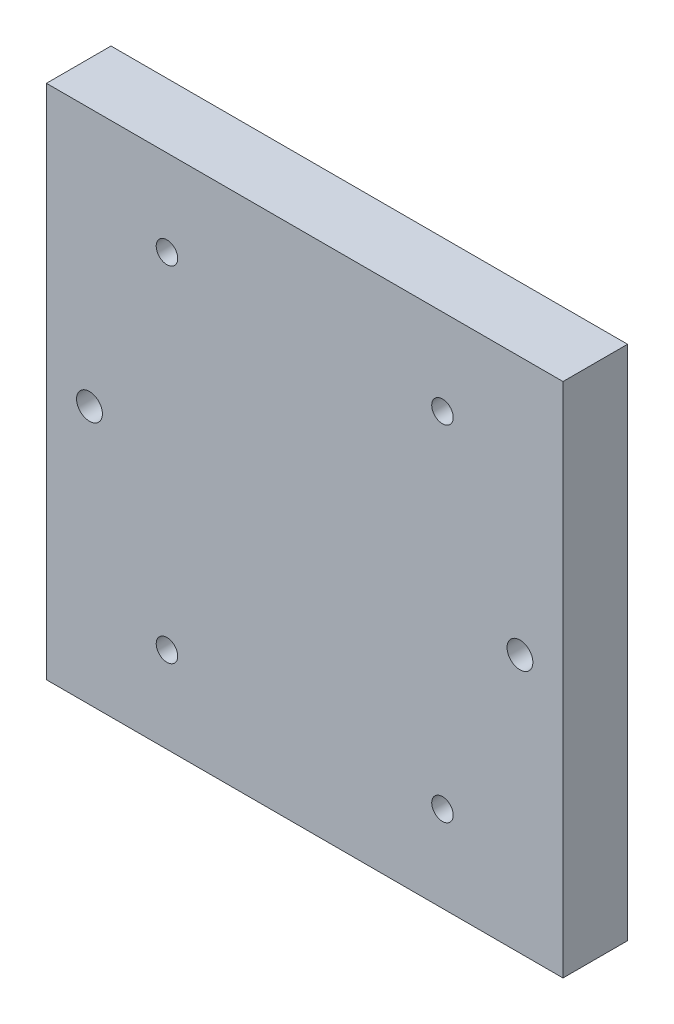
SolidWorks part; units mm, degrees
ref_plane "Front Plane" through (0, 0, 0) normal (0, 0, 1) x (1, 0, 0)
ref_plane "Top Plane" through (0, 0, 0) normal (0, 1, 0) x (1, 0, 0)
ref_plane "Right Plane" through (0, 0, 0) normal (1, 0, 0) x (0, 0, -1)
sketch "Sketch1" plane through (0, 0, 0) normal (0, 0, 1) x (1, 0, 0)
  line L1 (-60, 60) -> (60, 60)
  line L2 (-60, 60) -> (-60, -60)
  line L3 (-60, -60) -> (60, -60)
  line L4 (60, 60) -> (60, -60)
  line L5 (-60, 60) -> (60, -60) construction
  line L6 (-60, -60) -> (60, 60) construction
  point P0 (0, 0)
  dimension "D1" = 120
  dimension "D2" = 120
extrude "Boss-Extrude1" add sketch "Sketch1" against normal blind 15
sketch "Sketch7" plane through (0, 0, -15) normal (0, 0, -1) x (-1, 0, 0)
  line L0 (0, 0) -> (0, 40) construction
  line L1 (0, 0) -> (50, 0) construction
  line L3 (0, 0) -> (-32, 0) construction
  line L4 (-32, 0) -> (-32, -40) construction
  circle A4 centre (-32, -40) radius 2.5
  circle A5 centre (-32, 40) radius 2.5
  circle A6 centre (32, -40) radius 2.5
  circle A7 centre (32, 40) radius 2.5
  circle A8 centre (50, 0) radius 3
  circle A9 centre (-50, 0) radius 3
extrude "Cut-Extrude4" cut sketch "Sketch7" against normal up to next
